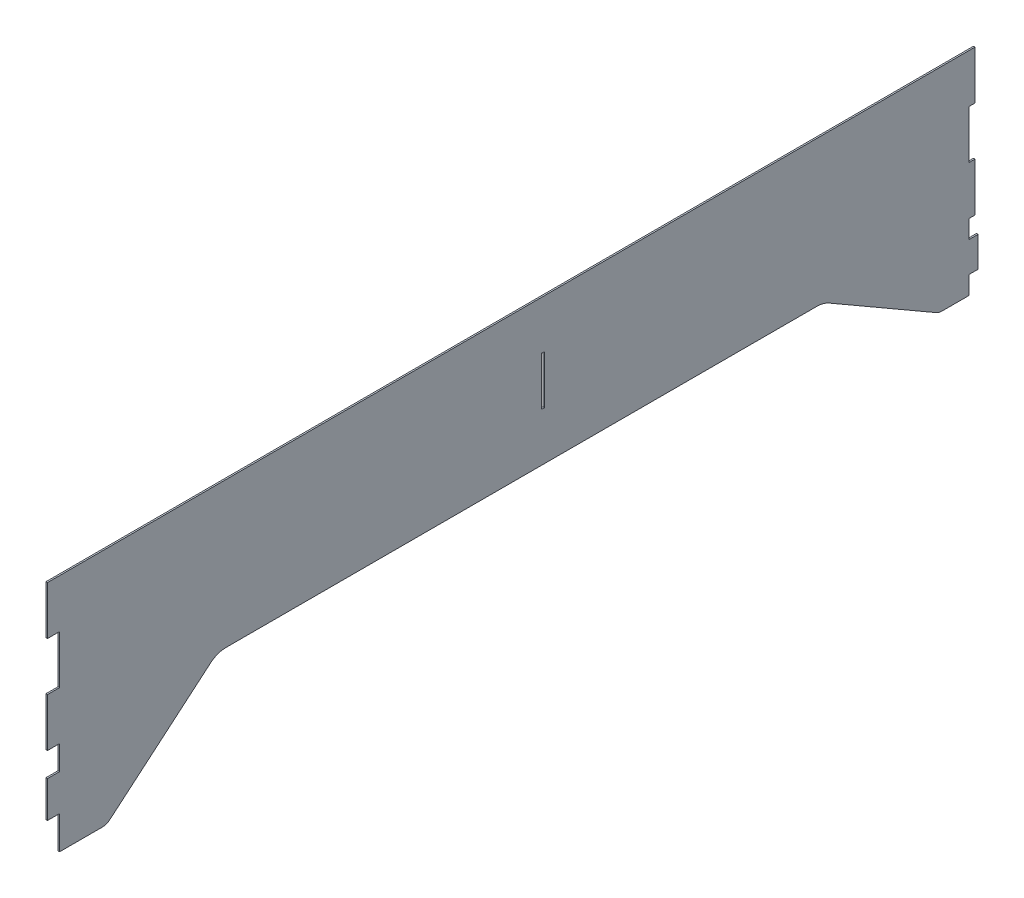
SolidWorks part; units mm, degrees
material "Thornel Mat VMA"
ref_plane "Front Plane" through (0, 0, 0) normal (0, 0, 1) x (1, 0, 0)
ref_plane "Top Plane" through (0, 0, 0) normal (0, 1, 0) x (1, 0, 0)
ref_plane "Right Plane" through (0, 0, 0) normal (1, 0, 0) x (0, 0, -1)
ref_plane "Plane1" through (-94.488, 0, 0) normal (-1, 0, 0) x (0, -1, 0)
sketch "Sketch1" plane through (-94.488, 0, 0) normal (-1, 0, 0) x (0, -1, 0)
  line L0 (111.125, -457.2) -> (85.725, -457.2)
  line L1 (85.725, -457.2) -> (85.725, -455.6125)
  line L2 (85.725, -455.6125) -> (111.125, -455.6125)
  line L3 (111.125, -455.6125) -> (111.125, -457.2)
  line L4 (111.125, -203.2) -> (85.725, -203.2)
  line L5 (85.725, -203.2) -> (85.725, -196.85)
  line L6 (85.725, -196.85) -> (60.325, -196.85)
  line L7 (60.325, -196.85) -> (60.325, -682.625)
  line L8 (60.325, -682.625) -> (85.725, -682.625)
  line L9 (85.725, -682.625) -> (85.725, -679.45)
  line L10 (85.725, -679.45) -> (111.125, -679.45)
  line L11 (111.125, -679.45) -> (111.125, -682.625)
  line L12 (111.125, -682.625) -> (136.525, -682.625)
  line L13 (136.525, -682.625) -> (136.525, -196.85)
  line L14 (136.525, -196.85) -> (111.125, -196.85)
  line L15 (111.125, -196.85) -> (111.125, -203.2)
  line L16 (136.525, -196.85) -> (185.6232, -196.85) construction
  line L17 (185.6232, -196.85) -> (185.6232, -227.7965) construction
  line L18 (184.1182, -229.5729) -> (139.535, -282.1971)
  line L19 (136.525, -203.2) -> (149.225, -203.2)
  line L20 (149.225, -203.2) -> (149.225, -196.85)
  line L21 (168.275, -196.85) -> (168.275, -203.2)
  line L22 (168.275, -203.2) -> (185.6232, -203.2)
  line L23 (185.6232, -203.2) -> (185.6232, -225.4683)
  line L24 (168.275, -196.85) -> (149.225, -196.85)
  line L25 (136.525, -679.45) -> (146.05, -679.45)
  line L26 (146.05, -679.45) -> (146.05, -684.2125)
  line L27 (146.05, -684.2125) -> (161.925, -684.2125)
  line L28 (161.925, -684.2125) -> (161.925, -679.45)
  line L29 (161.925, -679.45) -> (171.45, -679.45)
  line L30 (171.45, -679.45) -> (171.45, -665.4434)
  line L31 (170.5993, -662.2684) -> (138.2265, -606.197)
  circle A0 centre (130.175, -666.75) radius 1.7526 construction
  circle A1 centre (130.175, -615.95) radius 1.7526 construction
  circle A2 centre (130.175, -565.15) radius 1.7526 construction
  circle A3 centre (130.175, -514.35) radius 1.7526 construction
  circle A4 centre (130.175, -463.55) radius 1.7526 construction
  circle A5 centre (130.175, -412.75) radius 1.7526 construction
  circle A6 centre (130.175, -361.95) radius 1.7526 construction
  circle A7 centre (130.175, -311.15) radius 1.7526 construction
  circle A8 centre (130.175, -260.35) radius 1.7526 construction
  circle A9 centre (130.175, -209.55) radius 1.7526 construction
  arc A10 (184.1182, -229.5729) -> (185.6232, -225.4683) centre (179.2732, -225.4683) ccw
  arc A11 (139.535, -282.1971) -> (136.525, -290.4065) centre (149.225, -290.4065) ccw
  arc A12 (136.525, -599.847) -> (138.2265, -606.197) centre (149.225, -599.847) ccw
  arc A13 (171.45, -665.4434) -> (170.5993, -662.2684) centre (165.1, -665.4434) ccw
  point P38 (136.525, -285.75)
  point P58 (136.525, -603.25)
  dimension "D14" = 12.7
  dimension "D15" = 6.35
  dimension "D21" = 12.7
  dimension "D22" = 6.35
  dimension "D1" = 222.25
  dimension "D2" = 485.775
  dimension "D3" = 76.2
  dimension "D4" = 3.175
  dimension "D5" = 6.35
  dimension "D6" = 25.4
  dimension "D7" = 25.4
  dimension "D8" = 1.5875
  dimension "D9" = 49.0982
  dimension "D10" = 82.55
  dimension "D11" = 40.271
  dimension "D12" = 19.05
  dimension "D13" = 12.7
  dimension "D16" = 9.525
  dimension "D17" = 34.925
  dimension "D18" = 15.875
  dimension "D19" = 30
  dimension "D20" = 76.2
  dimension "D23" = 4.7625
extrude "Boss-Extrude1" add sketch "Sketch1" against normal blind 0.7937
